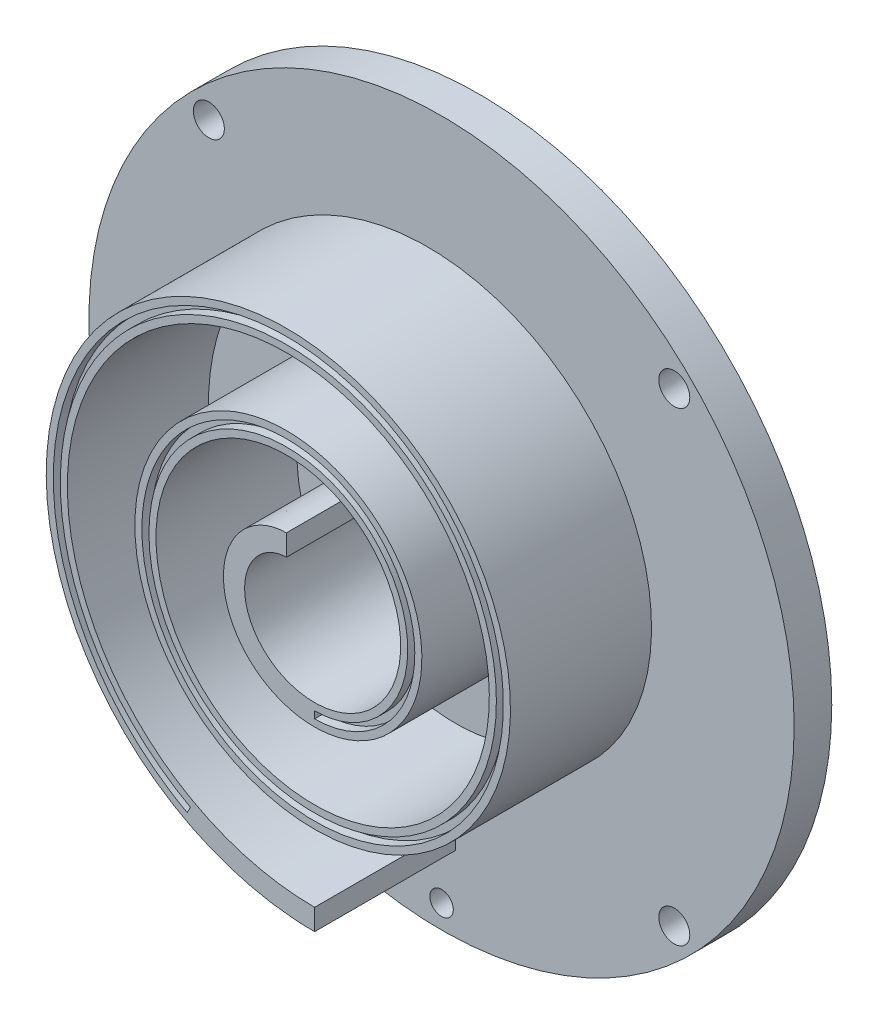
SolidWorks part; units mm, degrees
ref_plane "前视基准面" through (0, 0, 0) normal (0, 0, 1) x (1, 0, 0)
ref_plane "上视基准面" through (0, 0, 0) normal (0, 1, 0) x (1, 0, 0)
ref_plane "右视基准面" through (0, 0, 0) normal (1, 0, 0) x (0, 0, -1)
sketch "草图1" plane through (0, 0, 0) normal (0, 0, 1) x (1, 0, 0)
  circle A0 centre (0, 0) radius 75
extrude "凸台-拉伸1" add sketch "草图1" along normal blind 8
ref_plane "基准面1" through (0, 0, 8) normal (0, 0, 1) x (1, 0, 0)
sketch "草图2" plane through (0, 0, 0) normal (0, 0, 1) x (1, 0, 0)
  circle A0 centre (0, 0) radius 5
extrude "切除-拉伸1" cut sketch "草图2" along normal through all
sketch "草图3" plane through (0, 0, 8) normal (0, 0, 1) x (1, 0, 0)
  line L0 (3, -58.7987) -> (3, -54.2987)
  line L1 (-3, 7.1748) -> (-3, 11.6748)
  spline S0 degree 3 poles (-3, 11.6748) (-3.2407, 11.6705) (-3.7258, 11.6618) (-4.4563, 11.5916) (-5.1925, 11.4783) (-5.9313, 11.3168) (-6.6697, 11.1074) (-7.4046, 10.8494) (-8.1326, 10.5424) (-8.8506, 10.1863) (-9.5552, 9.7812) (-10.2431, 9.3275) (-10.9109, 8.8256) (-11.5552, 8.2764) (-12.1728, 7.6809) (-12.7604, 7.0403) (-13.3147, 6.3561) (-13.8325, 5.63) (-14.3109, 4.8639) (-14.7467, 4.06) (-15.1372, 3.2207) (-15.4797, 2.3485) (-15.7715, 1.4461) (-16.0102, 0.5166) (-16.1936, -0.4368) (-16.3196, -1.411) (-16.3865, -2.4023) (-16.3925, -3.4071) (-16.3362, -4.4217) (-16.2165, -5.4421) (-16.0325, -6.4644) (-15.7834, -7.4845) (-15.4689, -8.4982) (-15.0889, -9.5013) (-14.6434, -10.4894) (-14.1329, -11.4584) (-13.558, -12.404) (-12.9198, -13.3217) (-12.2196, -14.2075) (-11.4588, -15.0571) (-10.6393, -15.8664) (-9.7631, -16.6313) (-8.8328, -17.348) (-7.851, -18.0126) (-6.8205, -18.6215) (-5.7445, -19.1712) (-4.6265, -19.6584) (-3.4701, -20.08) (-2.2792, -20.4331) (-1.0579, -20.715) (0.1896, -20.9234) (1.4587, -21.0561) (2.7449, -21.1112) (4.0433, -21.0872) (5.3491, -20.9826) (6.6572, -20.7966) (7.9625, -20.5284) (9.2598, -20.1778) (10.5439, -19.7447) (11.8094, -19.2293) (13.0512, -18.6325) (14.2639, -17.9551) (15.4423, -17.1985) (16.5811, -16.3644) (17.6754, -15.4549) (18.7201, -14.4721) (19.7103, -13.419) (20.6413, -12.2984) (21.5085, -11.1137) (22.3075, -9.8686) (23.0342, -8.5669) (23.6845, -7.213) (24.2549, -5.8112) (24.7419, -4.3664) (25.1423, -2.8836) (25.4533, -1.3679) (25.6723, 0.1752) (25.7972, 1.7401) (25.8262, 3.3209) (25.7576, 4.9119) (25.5905, 6.5069) (25.324, 8.0999) (24.9577, 9.6844) (24.4918, 11.2544) (23.9266, 12.8035) (23.263, 14.3253) (22.5021, 15.8137) (21.6457, 17.2623) (20.6957, 18.6651) (19.6546, 20.0159) (18.5251, 21.3088) (17.3106, 22.5381) (16.0146, 23.6981) (14.641, 24.7835) (13.1941, 25.789) (11.6787, 26.7098) (10.0996, 27.5412) (8.4622, 28.2789) (6.7722, 28.9188) (5.0352, 29.4571) (3.2576, 29.8907) (1.4455, 30.2164) (-0.3943, 30.4317) (-2.2551, 30.5344) (-4.13, 30.5227) (-6.012, 30.3953) (-7.8938, 30.1513) (-9.7682, 29.7902) (-11.6279, 29.3121) (-13.4655, 28.7173) (-15.2737, 28.0068) (-17.0451, 27.1821) (-18.7726, 26.2448) (-20.449, 25.1974) (-22.0672, 24.0427) (-23.6203, 22.7837) (-25.1016, 21.4243) (-26.5045, 19.9684) (-27.8229, 18.4206) (-29.0508, 16.7859) (-30.1822, 15.0695) (-31.2119, 13.2772) (-32.1348, 11.415) (-32.9462, 9.4892) (-33.6417, 7.5067) (-34.2173, 5.4744) (-34.6697, 3.3996) (-34.9958, 1.2898) (-35.1928, -0.8473) (-35.2588, -3.0038) (-35.1921, -5.1715) (-34.9916, -7.3423) (-34.6566, -9.5079) (-34.187, -11.66) (-33.5833, -13.79) (-32.8463, -15.8897) (-31.9776, -17.9507) (-30.9791, -19.9646) (-29.8534, -21.9233) (-28.6034, -23.8188) (-27.2328, -25.643) (-25.7456, -27.3884) (-24.1463, -29.0474) (-22.44, -30.6129) (-20.6321, -32.0779) (-18.7285, -33.4359) (-16.7357, -34.6805) (-14.6604, -35.806) (-12.5097, -36.8069) (-10.2912, -37.6782) (-8.0127, -38.4153) (-5.6823, -39.014) (-3.3085, -39.4709) (-0.9, -39.7828) (1.5345, -39.9472) (3.9857, -39.9621) (6.4445, -39.826) (8.9016, -39.5381) (11.3475, -39.098) (13.7727, -38.5061) (16.168, -37.7633) (18.5237, -36.8709) (20.8306, -35.8312) (23.0794, -34.6467) (25.2609, -33.3206) (27.3664, -31.8569) (29.387, -30.2597) (31.3142, -28.5342) (32.8341, -26.9953) (33.9954, -25.706) (34.8391, -24.7095) (35.6535, -23.6854) (36.4379, -22.6345) (37.1913, -21.5578) (37.9128, -20.456) (38.6017, -19.3303) (39.2572, -18.1815) (39.8784, -17.0106) (40.4646, -15.8187) (41.0152, -14.6068) (41.5294, -13.3759) (42.0067, -12.1273) (42.4463, -10.8619) (42.8478, -9.5809) (43.2105, -8.2856) (43.534, -6.9769) (43.8178, -5.6562) (44.0615, -4.3246) (44.2647, -2.9834) (44.4269, -1.6337) (44.5479, -0.277) (44.6274, 1.0857) (44.6652, 2.453) (44.6609, 3.8237) (44.6146, 5.1963) (44.5259, 6.5698) (44.3949, 7.9426) (44.2216, 9.3137) (44.0057, 10.6815) (43.7476, 12.0449) (43.4471, 13.4024) (43.1044, 14.7528) (42.7196, 16.0948) (42.293, 17.4271) (41.8249, 18.7483) (41.3153, 20.0571) (40.7648, 21.3523) (40.1736, 22.6326) (39.5422, 23.8967) (38.8709, 25.1433) (38.1603, 26.3711) (37.4109, 27.579) (36.6232, 28.7657) (35.7979, 29.9299) (34.9355, 31.0706) (34.0368, 32.1864) (33.1024, 33.2763) (32.1331, 34.3391) (31.1298, 35.3737) (30.0931, 36.379) (29.024, 37.354) (27.9233, 38.2975) (26.7921, 39.2086) (25.6311, 40.0863) (24.4415, 40.9295) (23.2242, 41.7375) (21.9803, 42.5092) (20.7109, 43.2438) (19.4171, 43.9405) (18.0999, 44.5984) (16.7607, 45.2168) (15.4005, 45.7949) (14.0205, 46.332) (12.6221, 46.8275) (11.2065, 47.2807) (9.7749, 47.6911) (8.3286, 48.0581) (6.8691, 48.3811) (5.3975, 48.6598) (3.9153, 48.8936) (2.4238, 49.0821) (0.9244, 49.2252) (-0.5815, 49.3223) (-2.0925, 49.3733) (-3.6072, 49.3779) (-5.1241, 49.336) (-6.6418, 49.2474) (-8.1589, 49.112) (-9.674, 48.9299) (-11.1855, 48.7009) (-12.6921, 48.4251) (-14.1923, 48.1027) (-15.6846, 47.7338) (-17.1676, 47.3184) (-18.6399, 46.8569) (-20.1, 46.3496) (-21.5465, 45.7967) (-22.9779, 45.1986) (-24.3929, 44.5557) (-25.7901, 43.8685) (-27.168, 43.1373) (-28.5253, 42.3629) (-29.8606, 41.5458) (-31.1725, 40.6865) (-32.4599, 39.7857) (-33.7212, 38.8442) (-34.9553, 37.8627) (-36.1608, 36.842) (-37.3365, 35.7828) (-38.4813, 34.6862) (-39.5938, 33.5529) (-40.673, 32.384) (-41.7177, 31.1804) (-42.7267, 29.9431) (-43.6991, 28.6732) (-44.6336, 27.3718) (-45.5294, 26.04) (-46.3854, 24.679) (-47.2007, 23.2899) (-47.9744, 21.8739) (-48.7055, 20.4324) (-49.3933, 18.9666) (-50.0369, 17.4778) (-50.6355, 15.9673) (-51.1885, 14.4365) (-51.6952, 12.8867) (-52.1549, 11.3195) (-52.567, 9.7361) (-52.931, 8.1381) (-53.2463, 6.5269) (-53.5125, 4.9041) (-53.7292, 3.271) (-53.896, 1.6292) (-54.0125, -0.0197) (-54.0785, -1.6743) (-54.0937, -3.3329) (-54.058, -4.9941) (-53.9713, -6.6561) (-53.8333, -8.3176) (-53.6441, -9.9768) (-53.4037, -11.6323) (-53.1122, -13.2823) (-52.7695, -14.9255) (-52.376, -16.5601) (-51.9318, -18.1845) (-51.4372, -19.7973) (-50.8923, -21.3968) (-50.2977, -22.9815) (-49.6537, -24.5499) (-48.9607, -26.1003) (-48.2193, -27.6312) (-47.43, -29.1412) (-46.5933, -30.6288) (-45.7099, -32.0924) (-44.7805, -33.5306) (-43.8058, -34.9419) (-42.7866, -36.3249) (-41.7237, -37.6782) (-40.618, -39.0005) (-39.4704, -40.2903) (-38.2818, -41.5464) (-37.0533, -42.7674) (-35.7858, -43.9521) (-34.4804, -45.0992) (-33.1383, -46.2076) (-31.7606, -47.2759) (-30.3484, -48.3032) (-28.9031, -49.2882) (-27.4259, -50.23) (-25.9181, -51.1275) (-24.381, -51.9796) (-22.8159, -52.7855) (-21.2243, -53.5442) (-19.6076, -54.2549) (-17.9673, -54.9167) (-16.3047, -55.5289) (-14.6215, -56.0907) (-12.9192, -56.6014) (-11.1992, -57.0603) (-9.4632, -57.4669) (-7.7129, -57.8207) (-5.9497, -58.121) (-4.1753, -58.3675) (-2.3914, -58.56) (-0.5996, -58.6968) (1.1984, -58.7827) (2.3992, -58.7934) (3, -58.7987) knots 0 0 0 0 0.001304 0.002629 0.003974 0.00534 0.006726 0.008132 0.009559 0.011006 0.012474 0.013962 0.01547 0.016999 0.018548 0.020118 0.021708 0.023318 0.024949 0.0266 0.028272 0.029964 0.031677 0.03341 0.035163 0.036937 0.038731 0.040545 0.04238 0.044235 0.046111 0.048007 0.049924 0.051861 0.053818 0.055796 0.057794 0.059812 0.061851 0.063911 0.06599 0.06809 0.070211 0.072352 0.074513 0.076695 0.078897 0.08112 0.083363 0.085626 0.08791 0.090214 0.092539 0.094884 0.097249 0.099635 0.102042 0.104468 0.106915 0.109383 0.111871 0.114379 0.116908 0.119457 0.122026 0.124616 0.127226 0.129857 0.132508 0.13518 0.137871 0.140584 0.143317 0.14607 0.148843 0.151637 0.154451 0.157286 0.160141 0.163017 0.165913 0.168829 0.171766 0.174723 0.177701 0.180699 0.183717 0.186756 0.189815 0.192895 0.195995 0.199115 0.202256 0.205417 0.208599 0.211801 0.215023 0.218266 0.22153 0.224813 0.228117 0.231442 0.234787 0.238152 0.241538 0.244944 0.24837 0.251817 0.255284 0.258772 0.26228 0.265809 0.269358 0.272927 0.276517 0.280127 0.283757 0.287408 0.29108 0.294772 0.298484 0.302216 0.305969 0.309743 0.313536 0.317351 0.321185 0.32504 0.328916 0.332811 0.336728 0.340664 0.344621 0.348599 0.352597 0.356615 0.360654 0.364713 0.368792 0.372892 0.377012 0.381153 0.385314 0.389495 0.393697 0.39792 0.402162 0.406425 0.410709 0.415013 0.419337 0.423682 0.428047 0.432433 0.436839 0.441265 0.445712 0.450179 0.454666 0.459174 0.463703 0.468252 0.472821 0.47741 0.48202 0.486651 0.491302 0.495973 0.500664 0.503018 0.505377 0.507741 0.51011 0.512484 0.514863 0.517248 0.519637 0.522032 0.524431 0.526836 0.529246 0.531661 0.534081 0.536506 0.538936 0.541372 0.543812 0.546258 0.548709 0.551164 0.553625 0.556091 0.558562 0.561038 0.56352 0.566006 0.568498 0.570994 0.573496 0.576003 0.578515 0.581032 0.583554 0.586081 0.588613 0.591151 0.593693 0.596241 0.598793 0.601351 0.603914 0.606482 0.609055 0.611634 0.614217 0.616805 0.619399 0.621997 0.624601 0.62721 0.629824 0.632443 0.635067 0.637696 0.640331 0.64297 0.645615 0.648264 0.650919 0.653579 0.656244 0.658914 0.661589 0.664269 0.666955 0.669645 0.672341 0.675041 0.677747 0.680458 0.683174 0.685895 0.688621 0.691353 0.694089 0.69683 0.699577 0.702329 0.705085 0.707847 0.710614 0.713386 0.716164 0.718946 0.721733 0.724526 0.727323 0.730126 0.732934 0.735747 0.738565 0.741388 0.744216 0.74705 0.749888 0.752731 0.75558 0.758434 0.761293 0.764157 0.767026 0.7699 0.772779 0.775663 0.778553 0.781447 0.784347 0.787252 0.790162 0.793076 0.795997 0.798922 0.801852 0.804787 0.807728 0.810673 0.813624 0.81658 0.819541 0.822507 0.825478 0.828454 0.831435 0.834421 0.837413 0.840409 0.843411 0.846418 0.84943 0.852447 0.855469 0.858496 0.861528 0.864566 0.867608 0.870656 0.873709 0.876766 0.879829 0.882897 0.88597 0.889049 0.892132 0.89522 0.898314 0.901412 0.904516 0.907625 0.910739 0.913858 0.916982 0.920111 0.923246 0.926385 0.92953 0.932679 0.935834 0.938994 0.942159 0.945329 0.948504 0.951684 0.954869 0.95806 0.961255 0.964456 0.967662 0.970873 0.974089 0.97731 0.980536 0.983767 0.987004 0.990245 0.993492 0.996743 1 1 1 1
  spline S1 degree 3 poles (3, -54.2987) (2.4452, -54.2938) (1.3365, -54.2839) (-0.3236, -54.2046) (-1.9777, -54.0783) (-3.6243, -53.9006) (-5.262, -53.6732) (-6.889, -53.396) (-8.5041, -53.0696) (-10.1056, -52.6945) (-11.6922, -52.2711) (-13.2623, -51.8001) (-14.8145, -51.2821) (-16.3475, -50.7176) (-17.8598, -50.1075) (-19.3501, -49.4523) (-20.817, -48.753) (-22.2593, -48.0104) (-23.6757, -47.2251) (-25.0649, -46.3983) (-26.4257, -45.5308) (-27.7569, -44.6235) (-29.0574, -43.6774) (-30.326, -42.6937) (-31.5616, -41.6733) (-32.7633, -40.6173) (-33.9299, -39.5269) (-35.0605, -38.4032) (-36.1542, -37.2474) (-37.21, -36.0608) (-38.2272, -34.8444) (-39.2048, -33.5997) (-40.1421, -32.3278) (-41.0383, -31.0301) (-41.8927, -29.7079) (-42.7048, -28.3625) (-43.4738, -26.9953) (-44.1992, -25.6077) (-44.8804, -24.201) (-45.5171, -22.7766) (-46.1086, -21.336) (-46.6547, -19.8806) (-47.155, -18.4118) (-47.6092, -16.931) (-48.017, -15.4397) (-48.3782, -13.9394) (-48.6926, -12.4314) (-48.9602, -10.9173) (-49.1807, -9.3985) (-49.3543, -7.8764) (-49.4808, -6.3526) (-49.5604, -4.8284) (-49.5931, -3.3053) (-49.5791, -1.7847) (-49.5187, -0.2682) (-49.4119, 1.243) (-49.259, 2.7475) (-49.0605, 4.2437) (-48.8167, 5.7303) (-48.5279, 7.206) (-48.1946, 8.6693) (-47.8172, 10.1191) (-47.3964, 11.5538) (-46.9326, 12.9723) (-46.4265, 14.3733) (-45.8788, 15.7554) (-45.2899, 17.1175) (-44.6608, 18.4583) (-43.9922, 19.7767) (-43.2847, 21.0715) (-42.5393, 22.3415) (-41.7568, 23.5857) (-40.9381, 24.8029) (-40.0841, 25.9922) (-39.1957, 27.1524) (-38.2739, 28.2827) (-37.3197, 29.382) (-36.3342, 30.4495) (-35.3184, 31.4842) (-34.2734, 32.4854) (-33.2002, 33.4521) (-32.1, 34.3836) (-30.974, 35.2792) (-29.8233, 36.1381) (-28.6492, 36.9597) (-27.4527, 37.7433) (-26.2352, 38.4884) (-24.9978, 39.1944) (-23.7419, 39.8608) (-22.4686, 40.4871) (-21.1793, 41.0729) (-19.8753, 41.6178) (-18.5578, 42.1214) (-17.2281, 42.5834) (-15.8876, 43.0036) (-14.5375, 43.3817) (-13.1792, 43.7175) (-11.814, 44.0109) (-10.4433, 44.2618) (-9.0683, 44.4701) (-7.6903, 44.6358) (-6.3107, 44.7589) (-4.9308, 44.8394) (-3.5519, 44.8775) (-2.1753, 44.8733) (-0.8024, 44.827) (0.5658, 44.7388) (1.9277, 44.6089) (3.2822, 44.4376) (4.628, 44.2253) (5.964, 43.9724) (7.2887, 43.6792) (8.6011, 43.3462) (9.9, 42.9738) (11.1841, 42.5627) (12.4524, 42.1133) (13.7037, 41.6263) (14.9368, 41.1022) (16.1507, 40.5417) (17.3443, 39.9455) (18.5166, 39.3143) (19.6665, 38.6488) (20.7931, 37.9499) (21.8953, 37.2183) (22.9723, 36.4549) (24.0231, 35.6605) (25.0468, 34.836) (26.0427, 33.9823) (27.0097, 33.1004) (27.9473, 32.1913) (28.8545, 31.2558) (30.0215, 29.9762) (31.4013, 28.316) (32.9267, 26.233) (34.3153, 24.0698) (35.5632, 21.8355) (36.6669, 19.539) (37.6234, 17.1896) (38.4304, 14.7967) (39.0862, 12.3697) (39.5897, 9.9181) (39.9403, 7.4515) (40.1381, 4.9792) (40.1837, 2.5108) (40.0784, 0.0556) (39.8238, -2.3774) (39.4224, -4.779) (38.8771, -7.1405) (38.1912, -9.4532) (37.3686, -11.709) (36.4138, -13.8996) (35.3315, -16.0176) (34.1272, -18.0555) (32.8065, -20.0063) (31.3756, -21.8635) (29.8409, -23.621) (28.2093, -25.273) (26.4879, -26.8143) (24.684, -28.2402) (22.8054, -29.5463) (20.8599, -30.7288) (18.8556, -31.7846) (16.8005, -32.7109) (14.7032, -33.5054) (12.5718, -34.1664) (10.4149, -34.6928) (8.2408, -35.084) (6.0582, -35.3398) (3.8752, -35.4606) (1.7002, -35.4474) (-0.4586, -35.3017) (-2.5932, -35.0253) (-4.6958, -34.6206) (-6.7586, -34.0906) (-8.7743, -33.4386) (-10.7357, -32.6683) (-12.6359, -31.784) (-14.4684, -30.7902) (-16.2269, -29.6919) (-17.9056, -28.4944) (-19.4989, -27.2033) (-21.0017, -25.8246) (-22.4092, -24.3645) (-23.7173, -22.8294) (-24.922, -21.226) (-26.0199, -19.5612) (-27.008, -17.842) (-27.8838, -16.0756) (-28.6452, -14.2692) (-29.2907, -12.4301) (-29.8191, -10.5659) (-30.2298, -8.6837) (-30.5226, -6.7911) (-30.6978, -4.8954) (-30.756, -3.0038) (-30.6985, -1.1234) (-30.5268, 0.7386) (-30.243, 2.5754) (-29.8495, 4.3803) (-29.3491, 6.1469) (-28.7451, 7.8687) (-28.041, 9.5399) (-27.2408, 11.1546) (-26.3487, 12.7074) (-25.3693, 14.1931) (-24.3074, 15.607) (-23.1682, 16.9445) (-21.9569, 18.2014) (-20.6791, 19.3741) (-19.3407, 20.4591) (-17.9474, 21.4535) (-16.5053, 22.3545) (-15.0206, 23.16) (-13.4996, 23.8682) (-11.9485, 24.4777) (-10.3737, 24.9874) (-8.7816, 25.3968) (-7.1785, 25.7056) (-5.5706, 25.9141) (-3.9643, 26.0229) (-2.3656, 26.0329) (-0.7806, 25.9454) (0.7848, 25.7623) (2.325, 25.4855) (3.8343, 25.1174) (5.3073, 24.6609) (6.7391, 24.1188) (8.1246, 23.4947) (9.4592, 22.792) (10.7386, 22.0146) (11.9586, 21.1668) (13.1155, 20.2527) (14.2057, 19.2769) (15.2261, 18.2442) (16.1738, 17.1593) (17.0463, 16.0273) (17.8414, 14.8533) (18.5573, 13.6425) (19.1924, 12.4001) (19.7457, 11.1315) (20.2162, 9.842) (20.6036, 8.5368) (20.9076, 7.2214) (21.1286, 5.901) (21.267, 4.5807) (21.3237, 3.2657) (21.2998, 1.961) (21.1969, 0.6715) (21.0167, -0.5981) (20.7613, -1.8432) (20.433, -3.0593) (20.0342, -4.2424) (19.568, -5.3883) (19.0373, -6.4932) (18.4453, -7.5537) (17.7955, -8.5663) (17.0915, -9.5281) (16.3371, -10.4363) (15.5361, -11.2882) (14.6927, -12.0816) (13.8109, -12.8146) (12.8949, -13.4855) (11.949, -14.0929) (10.9775, -14.6356) (9.9847, -15.1128) (8.975, -15.524) (7.9527, -15.8689) (6.9221, -16.1475) (5.8874, -16.3601) (4.8528, -16.5072) (3.8224, -16.5898) (2.8002, -16.6087) (1.79, -16.5655) (0.7956, -16.4616) (-0.1794, -16.2987) (-1.1316, -16.0789) (-2.0576, -15.8044) (-2.9545, -15.4775) (-3.8193, -15.1007) (-4.6493, -14.6767) (-5.442, -14.2083) (-6.1951, -13.6986) (-6.9066, -13.1506) (-7.5746, -12.5673) (-8.1976, -11.9522) (-8.7742, -11.3084) (-9.3031, -10.6394) (-9.7837, -9.9485) (-10.215, -9.239) (-10.5968, -8.5144) (-10.9288, -7.7781) (-11.211, -7.0334) (-11.4437, -6.2836) (-11.6273, -5.5319) (-11.7624, -4.7814) (-11.85, -4.0353) (-11.891, -3.2966) (-11.8867, -2.568) (-11.8385, -1.8523) (-11.7479, -1.1521) (-11.6168, -0.4699) (-11.4468, 0.192) (-11.2401, 0.8315) (-10.9986, 1.4466) (-10.7247, 2.0355) (-10.4206, 2.5966) (-9.9821, 3.299) (-9.3721, 4.1026) (-8.5516, 4.9455) (-7.6694, 5.6534) (-6.7457, 6.224) (-5.8002, 6.6592) (-4.8518, 6.9591) (-3.9181, 7.1413) (-3.301, 7.1638) (-3, 7.1748) knots 0 0 0 0 0.003448 0.00689 0.010326 0.013756 0.01718 0.020598 0.024011 0.027418 0.030819 0.034214 0.037603 0.040986 0.044364 0.047735 0.051101 0.054461 0.057815 0.061163 0.064506 0.067842 0.071173 0.074498 0.077817 0.08113 0.084437 0.087739 0.091035 0.094324 0.097608 0.100886 0.104159 0.107425 0.110685 0.11394 0.117189 0.120432 0.123669 0.1269 0.130126 0.133345 0.136559 0.139767 0.142969 0.146165 0.149355 0.15254 0.155719 0.158891 0.162058 0.165219 0.168375 0.171524 0.174668 0.177805 0.180937 0.184063 0.187183 0.190297 0.193406 0.196509 0.199605 0.202696 0.205781 0.20886 0.211934 0.215001 0.218063 0.221119 0.224169 0.227213 0.230251 0.233283 0.23631 0.239331 0.242346 0.245355 0.248358 0.251355 0.254347 0.257332 0.260312 0.263286 0.266254 0.269216 0.272173 0.275123 0.278068 0.281007 0.28394 0.286867 0.289788 0.292703 0.295613 0.298517 0.301415 0.304307 0.307193 0.310073 0.312948 0.315816 0.318679 0.321536 0.324387 0.327232 0.330072 0.332905 0.335733 0.338555 0.341371 0.344181 0.346985 0.349784 0.352576 0.355363 0.358144 0.360919 0.363688 0.366452 0.369209 0.371961 0.374707 0.377447 0.380181 0.382909 0.385631 0.388348 0.391059 0.393764 0.396463 0.399156 0.404524 0.409869 0.41519 0.420488 0.425763 0.431014 0.436242 0.441446 0.446627 0.451785 0.456919 0.46203 0.467117 0.472181 0.477222 0.482239 0.487233 0.492204 0.497151 0.502074 0.506975 0.511852 0.516705 0.521535 0.526342 0.531125 0.535885 0.540622 0.545335 0.550025 0.554691 0.559334 0.563954 0.56855 0.573123 0.577672 0.582198 0.586701 0.59118 0.595636 0.600068 0.604477 0.608863 0.613225 0.617564 0.621879 0.626172 0.63044 0.634686 0.638907 0.643106 0.647281 0.651433 0.655561 0.659666 0.663748 0.667806 0.671841 0.675852 0.67984 0.683804 0.687746 0.691663 0.695558 0.699429 0.703277 0.707101 0.710902 0.714679 0.718433 0.722164 0.725871 0.729555 0.733215 0.736852 0.740466 0.744056 0.747623 0.751167 0.754687 0.758184 0.761657 0.765107 0.768533 0.771937 0.775316 0.778673 0.782006 0.785315 0.788601 0.791864 0.795104 0.79832 0.801512 0.804681 0.807827 0.81095 0.814049 0.817124 0.820177 0.823205 0.826211 0.829193 0.832152 0.835087 0.837999 0.840887 0.843752 0.846594 0.849413 0.852207 0.854979 0.857727 0.860452 0.863153 0.865831 0.868486 0.871117 0.873725 0.876309 0.87887 0.881408 0.883922 0.886413 0.88888 0.891324 0.893745 0.896142 0.898516 0.900866 0.903193 0.905497 0.907777 0.910034 0.912268 0.914478 0.916665 0.918828 0.920968 0.923084 0.925178 0.927247 0.929294 0.931317 0.933316 0.935292 0.937245 0.939174 0.94108 0.942963 0.944822 0.946658 0.948471 0.95026 0.952025 0.953767 0.955486 0.957182 0.958854 0.960502 0.962128 0.96373 0.965308 0.966863 0.968395 0.969903 0.971388 0.97285 0.974288 0.975703 0.977094 0.978462 0.979806 0.981128 0.982425 0.98495 0.98738 0.989717 0.991961 0.994111 0.996168 0.998131 1 1 1 1
extrude "凸台-拉伸2" add sketch "草图3" along normal blind 30
sketch "草图4" plane through (0, 0, 0) normal (0, 0, 1) x (1, 0, 0)
  circle A0 centre (49.4975, 49.4975) radius 3.3
  circle A1 centre (-49.4975, 49.4975) radius 3.3
  circle A2 centre (-49.4975, -49.4975) radius 3.3
  circle A3 centre (49.4975, -49.4975) radius 3.3
extrude "切除-拉伸2" cut sketch "草图4" along normal through all
sketch "草图5" plane through (0, 0, 0) normal (0, 0, 1) x (1, 0, 0)
  circle A0 centre (0, -70) radius 2.5
extrude "切除-拉伸3" cut sketch "草图5" along normal through all
ref_plane "基准面2" through (0, 0, 38) normal (0, 0, 1) x (1, 0, 0)
sketch "草图6" plane through (0, 0, 38) normal (0, 0, 1) x (1, 0, 0)
  line L0 (-24.1186, -50.4062) -> (-23.3995, -49.0899)
  line L1 (3, -18.0996) -> (3, -19.5996)
  spline S0 degree 3 poles (3, -19.5996) (3.309, -19.5953) (3.9294, -19.5869) (4.8611, -19.5183) (5.7953, -19.4083) (6.7298, -19.2524) (7.6625, -19.0516) (8.5911, -18.8052) (9.5134, -18.5134) (10.4272, -18.1761) (11.3303, -17.7935) (12.2203, -17.3659) (13.0951, -16.8937) (13.9523, -16.3774) (14.7898, -15.8175) (15.6054, -15.2149) (16.3968, -14.5703) (17.1619, -13.8846) (17.8987, -13.159) (18.6049, -12.3946) (19.2787, -11.5926) (19.9179, -10.7545) (20.5208, -9.8817) (21.0854, -8.9759) (21.6099, -8.0386) (22.0926, -7.0717) (22.532, -6.077) (22.9264, -5.0565) (23.2744, -4.0122) (23.5746, -2.9463) (23.8258, -1.8609) (24.0267, -0.7583) (24.1764, 0.3591) (24.2738, 1.489) (24.3181, 2.6289) (24.3086, 3.7762) (24.2447, 4.9285) (24.1259, 6.0832) (23.9518, 7.2375) (23.7222, 8.3889) (23.4371, 9.5347) (23.0963, 10.6722) (22.7001, 11.7986) (22.2488, 12.9113) (21.7427, 14.0075) (21.1825, 15.0846) (20.5688, 16.1399) (19.9025, 17.1707) (19.1844, 18.1743) (18.4158, 19.1483) (17.5977, 20.09) (16.7315, 20.9969) (15.8188, 21.8666) (14.861, 22.6967) (13.86, 23.4848) (12.8175, 24.2288) (11.7356, 24.9265) (10.6161, 25.5757) (9.4615, 26.1746) (8.2738, 26.7212) (7.0555, 27.2137) (5.8091, 27.6505) (4.5371, 28.0299) (3.2421, 28.3506) (1.9269, 28.6113) (0.5944, 28.8106) (-0.7527, 28.9477) (-2.1115, 29.0214) (-3.4789, 29.0312) (-4.8518, 28.9762) (-6.2273, 28.856) (-7.6022, 28.6702) (-8.9734, 28.4187) (-10.3378, 28.1013) (-11.692, 27.7182) (-13.033, 27.2696) (-14.3576, 26.7558) (-15.6627, 26.1776) (-16.945, 25.5355) (-18.2014, 24.8304) (-19.4289, 24.0634) (-20.6243, 23.2357) (-21.7848, 22.3484) (-22.9072, 21.4032) (-23.9887, 20.4016) (-25.0266, 19.3454) (-26.0179, 18.2365) (-26.9601, 17.077) (-27.8506, 15.869) (-28.6868, 14.6148) (-29.4665, 13.3169) (-30.1873, 11.9779) (-30.8472, 10.6003) (-31.4439, 9.1871) (-31.9757, 7.741) (-32.4408, 6.2652) (-32.8376, 4.7626) (-33.1645, 3.2365) (-33.4202, 1.6901) (-33.6036, 0.1267) (-33.7135, -1.4502) (-33.7492, -3.0372) (-33.7099, -4.6308) (-33.5951, -6.2274) (-33.4044, -7.8235) (-33.1376, -9.4154) (-32.7947, -10.9994) (-32.3758, -12.572) (-31.8813, -14.1294) (-31.3116, -15.6681) (-30.6674, -17.1844) (-29.9497, -18.6746) (-29.1593, -20.1352) (-28.2976, -21.5627) (-27.3658, -22.9535) (-26.3656, -24.3042) (-25.2986, -25.6115) (-24.1668, -26.872) (-22.9721, -28.0825) (-21.7169, -29.2399) (-20.4034, -30.3412) (-19.0341, -31.3834) (-17.6118, -32.3637) (-16.1392, -33.2794) (-14.6193, -34.128) (-13.0552, -34.9069) (-11.4499, -35.614) (-9.8069, -36.2471) (-8.1296, -36.8042) (-6.4215, -37.2834) (-4.6862, -37.6831) (-2.9274, -38.0018) (-1.1489, -38.2382) (0.6453, -38.391) (2.4514, -38.4594) (4.2654, -38.4426) (6.0833, -38.3399) (7.9009, -38.151) (9.7142, -37.8757) (11.519, -37.5139) (13.3113, -37.0659) (15.0869, -36.532) (16.8416, -35.9129) (18.5713, -35.2092) (20.2721, -34.422) (21.9398, -33.5525) (23.5704, -32.602) (25.16, -31.5721) (26.7047, -30.4646) (28.2008, -29.2813) (29.6445, -28.0246) (31.0322, -26.6966) (32.3603, -25.2998) (33.6256, -23.837) (34.8246, -22.3109) (35.9543, -20.7247) (37.0115, -19.0813) (37.9935, -17.3842) (38.8976, -15.6368) (39.721, -13.8427) (40.4616, -12.0055) (41.1169, -10.1293) (41.685, -8.2178) (42.164, -6.2753) (42.5522, -4.3057) (42.8482, -2.3135) (43.0507, -0.3029) (43.1585, 1.7216) (43.1709, 3.7556) (43.0872, 5.7947) (42.9068, 7.8341) (42.6297, 9.8694) (42.2559, 11.896) (41.7854, 13.9092) (41.2187, 15.9044) (40.5566, 17.8769) (39.7998, 19.8224) (38.9496, 21.736) (38.0071, 23.6135) (36.9739, 25.4503) (35.8518, 27.242) (34.6427, 28.9843) (33.3488, 30.673) (31.9725, 32.304) (30.5163, 33.8732) (28.983, 35.3767) (27.3757, 36.8107) (25.6973, 38.1716) (23.9514, 39.4559) (22.1413, 40.6602) (20.2708, 41.7813) (18.3436, 42.8161) (16.3639, 43.7619) (14.3356, 44.6159) (12.2631, 45.3758) (10.1507, 46.0391) (8.0029, 46.6038) (5.8244, 47.0681) (3.6199, 47.4304) (1.3941, 47.6891) (-0.848, 47.8431) (-3.1016, 47.8915) (-5.3616, 47.8335) (-7.623, 47.6685) (-9.8807, 47.3964) (-12.1297, 47.0171) (-14.3649, 46.5309) (-16.5811, 45.9381) (-18.7732, 45.2396) (-20.9363, 44.4362) (-23.0652, 43.5292) (-25.155, 42.52) (-27.2008, 41.4103) (-29.1978, 40.2019) (-31.1412, 38.8971) (-33.0262, 37.4982) (-34.8485, 36.0079) (-36.6034, 34.4288) (-38.2867, 32.7642) (-39.8943, 31.0171) (-41.422, 29.1912) (-42.866, 27.29) (-44.2226, 25.3173) (-45.4883, 23.2773) (-46.6597, 21.1741) (-47.7337, 19.0121) (-48.7072, 16.7957) (-49.5777, 14.5297) (-50.3426, 12.2189) (-50.9995, 9.8682) (-51.5464, 7.4827) (-51.9814, 5.0675) (-52.3031, 2.6279) (-52.51, 0.1691) (-52.6011, -2.3033) (-52.5756, -4.7839) (-52.4328, -7.2672) (-52.1724, -9.7477) (-51.7945, -12.2197) (-51.2992, -14.6778) (-50.687, -17.1162) (-49.9586, -19.5294) (-49.1152, -21.9119) (-48.1579, -24.2583) (-47.0883, -26.5629) (-45.9082, -28.8205) (-44.6197, -31.0258) (-43.2251, -33.1735) (-41.727, -35.2585) (-40.1282, -37.2758) (-38.4317, -39.2206) (-36.6408, -41.0881) (-34.7591, -42.8738) (-32.7902, -44.573) (-30.7386, -46.1823) (-28.6068, -47.6948) (-26.4047, -49.1167) (-24.8812, -49.976) (-24.1186, -50.4062) knots 0 0 0 0 0.002038 0.004091 0.006158 0.008241 0.010337 0.012449 0.014575 0.016716 0.018871 0.021041 0.023226 0.025425 0.027639 0.029868 0.032111 0.034369 0.036641 0.038929 0.041231 0.043547 0.045878 0.048224 0.050585 0.05296 0.05535 0.057754 0.060173 0.062607 0.065055 0.067518 0.069996 0.072488 0.074995 0.077517 0.080053 0.082604 0.08517 0.08775 0.090345 0.092955 0.095579 0.098218 0.100871 0.10354 0.106222 0.10892 0.111632 0.114359 0.1171 0.119856 0.122627 0.125413 0.128213 0.131027 0.133857 0.136701 0.139559 0.142433 0.145321 0.148223 0.15114 0.154072 0.157019 0.15998 0.162956 0.165947 0.168952 0.171972 0.175006 0.178055 0.181119 0.184197 0.18729 0.190398 0.193521 0.196658 0.199809 0.202976 0.206157 0.209352 0.212563 0.215788 0.219027 0.222281 0.22555 0.228834 0.232132 0.235445 0.238772 0.242115 0.245471 0.248843 0.252229 0.25563 0.259045 0.262475 0.26592 0.269379 0.272853 0.276342 0.279845 0.283363 0.286896 0.290443 0.294005 0.297582 0.301173 0.304779 0.308399 0.312035 0.315685 0.319349 0.323028 0.326722 0.33043 0.334154 0.337891 0.341644 0.345411 0.349192 0.352989 0.3568 0.360625 0.364466 0.368321 0.37219 0.376075 0.379974 0.383887 0.387815 0.391758 0.395716 0.399688 0.403675 0.407676 0.411692 0.415723 0.419769 0.423829 0.427904 0.431993 0.436097 0.440216 0.444349 0.448497 0.45266 0.456837 0.461029 0.465236 0.469457 0.473693 0.477943 0.482208 0.486488 0.490783 0.495092 0.499416 0.503754 0.508107 0.512475 0.516858 0.521255 0.525666 0.530093 0.534534 0.53899 0.54346 0.547945 0.552445 0.556959 0.561488 0.566031 0.57059 0.575163 0.57975 0.584352 0.588969 0.593601 0.598247 0.602908 0.607583 0.612273 0.616978 0.621697 0.626431 0.63118 0.635944 0.640722 0.645514 0.650322 0.655144 0.65998 0.664831 0.669697 0.674578 0.679473 0.684383 0.689308 0.694247 0.699201 0.704169 0.709152 0.71415 0.719163 0.72419 0.729231 0.734288 0.739359 0.744445 0.749545 0.75466 0.75979 0.764934 0.770093 0.775267 0.780455 0.785658 0.790875 0.796108 0.801354 0.806616 0.811892 0.817183 0.822488 0.827809 0.833143 0.838493 0.843857 0.849236 0.854629 0.860037 0.86546 0.870897 0.876349 0.881816 0.887297 0.892793 0.898304 0.903829 0.909369 0.914923 0.920493 0.926076 0.931675 0.937288 0.942916 0.948558 0.954216 0.959887 0.965574 0.971275 0.976991 0.982721 0.988466 0.994226 1 1 1 1
  spline S1 degree 3 poles (-23.3995, -49.0899) (-24.1416, -48.6712) (-25.6239, -47.835) (-27.7666, -46.4516) (-29.8407, -44.9799) (-31.8368, -43.4143) (-33.7521, -41.7613) (-35.5825, -40.0243) (-37.3244, -38.2079) (-38.9744, -36.3164) (-40.5294, -34.3545) (-41.9862, -32.3269) (-43.3423, -30.2385) (-44.5951, -28.0943) (-45.7424, -25.8994) (-46.7823, -23.6589) (-47.7128, -21.378) (-48.5327, -19.0622) (-49.2406, -16.7166) (-49.8356, -14.3468) (-50.3169, -11.9581) (-50.6841, -9.556) (-50.9371, -7.1459) (-51.0759, -4.7331) (-51.1007, -2.3232) (-51.0122, 0.0785) (-50.8112, 2.4668) (-50.4988, 4.8363) (-50.0763, 7.1819) (-49.5452, 9.4985) (-48.9073, 11.7811) (-48.1647, 14.0248) (-47.3196, 16.2247) (-46.3744, 18.3763) (-45.3319, 20.475) (-44.1949, 22.5165) (-42.9666, 24.4964) (-41.65, 26.4107) (-40.2488, 28.2556) (-38.7664, 30.0273) (-37.2068, 31.7223) (-35.5737, 33.3373) (-33.8714, 34.869) (-32.1039, 36.3146) (-30.2756, 37.6714) (-28.391, 38.9367) (-26.4545, 40.1085) (-24.4709, 41.1845) (-22.4447, 42.1629) (-20.3809, 43.0422) (-18.2841, 43.821) (-16.1593, 44.498) (-14.0115, 45.0725) (-11.8454, 45.5437) (-9.6662, 45.9113) (-7.4786, 46.1749) (-5.2878, 46.3347) (-3.0984, 46.391) (-0.9156, 46.3441) (1.256, 46.1949) (3.4115, 45.9444) (5.5463, 45.5936) (7.6556, 45.144) (9.7349, 44.5973) (11.7798, 43.9551) (13.786, 43.2197) (15.7491, 42.3931) (17.665, 41.4778) (19.5299, 40.4764) (21.3397, 39.3917) (23.0909, 38.2266) (24.7799, 36.9842) (26.4033, 35.6678) (27.9579, 34.2809) (29.4407, 32.8269) (30.8487, 31.3095) (32.1795, 29.7326) (33.4303, 28.1) (34.5991, 26.4158) (35.6837, 24.684) (36.6822, 22.9089) (37.593, 21.0947) (38.4146, 19.2456) (39.1457, 17.3661) (39.7853, 15.4606) (40.3326, 13.5334) (40.787, 11.5891) (41.1481, 9.6321) (41.4156, 7.6669) (41.5897, 5.6978) (41.6706, 3.7295) (41.6586, 1.7662) (41.5545, -0.1878) (41.3592, -2.128) (41.0736, -4.0503) (40.699, -5.9504) (40.237, -7.8243) (39.689, -9.6679) (39.057, -11.4774) (38.3429, -13.249) (37.549, -14.9788) (36.6774, -16.6634) (35.7308, -18.2993) (34.7118, -19.8832) (33.6232, -21.4119) (32.4679, -22.8823) (31.2489, -24.2917) (29.9695, -25.6372) (28.6329, -26.9163) (27.2425, -28.1266) (25.8019, -29.266) (24.3147, -30.3323) (22.7844, -31.3237) (21.2149, -32.2386) (19.6099, -33.0755) (17.9734, -33.8329) (16.3091, -34.51) (14.6211, -35.1056) (12.9133, -35.6191) (11.1896, -36.05) (9.4541, -36.3979) (7.7107, -36.6626) (5.9634, -36.8442) (4.2162, -36.9428) (2.4729, -36.959) (0.7375, -36.8933) (-0.9863, -36.7465) (-2.6947, -36.5194) (-4.3838, -36.2133) (-6.0502, -35.8295) (-7.6903, -35.3694) (-9.3005, -34.8346) (-10.8775, -34.227) (-12.418, -33.5484) (-13.9189, -32.8009) (-15.377, -31.9868) (-16.7896, -31.1085) (-18.1536, -30.1683) (-19.4666, -29.1689) (-20.7259, -28.1131) (-21.9292, -27.0037) (-23.0742, -25.8435) (-24.1587, -24.6356) (-25.181, -23.3831) (-26.1391, -22.0892) (-27.0315, -20.7572) (-27.8567, -19.3903) (-28.6134, -17.9918) (-29.3005, -16.5653) (-29.917, -15.1142) (-30.4621, -13.6418) (-30.9353, -12.1518) (-31.336, -10.6475) (-31.6639, -9.1326) (-31.919, -7.6105) (-32.1013, -6.0846) (-32.2111, -4.5586) (-32.2486, -3.0357) (-32.2146, -1.5194) (-32.1095, -0.013) (-31.9344, 1.4801) (-31.6902, 2.9568) (-31.3781, 4.4137) (-30.9995, 5.8479) (-30.5556, 7.2563) (-30.0482, 8.636) (-29.479, 9.9841) (-28.8497, 11.2979) (-28.1624, 12.5747) (-27.4191, 13.8119) (-26.6221, 15.0073) (-25.7736, 16.1584) (-24.876, 17.263) (-23.9318, 18.3192) (-22.9436, 19.3249) (-21.9139, 20.2785) (-20.8456, 21.1781) (-19.7413, 22.0224) (-18.604, 22.8099) (-17.4365, 23.5395) (-16.2418, 24.2099) (-15.0227, 24.8203) (-13.7823, 25.37) (-12.5237, 25.8581) (-11.2497, 26.2843) (-9.9635, 26.6482) (-8.6681, 26.9495) (-7.3664, 27.1883) (-6.0616, 27.3646) (-4.7566, 27.4786) (-3.4542, 27.5308) (-2.1576, 27.5216) (-0.8695, 27.4517) (0.4073, 27.3218) (1.6699, 27.1329) (2.9157, 26.886) (4.142, 26.5823) (5.3463, 26.2231) (6.526, 25.8097) (7.6787, 25.3437) (8.8021, 24.8267) (9.894, 24.2604) (10.9522, 23.6466) (11.9748, 22.9873) (12.9597, 22.2844) (13.9052, 21.5399) (14.8095, 20.7562) (15.671, 19.9353) (16.4883, 19.0795) (17.26, 18.1912) (17.9849, 17.2728) (18.6618, 16.3267) (19.2898, 15.3553) (19.8679, 14.3611) (20.3955, 13.3468) (20.8719, 12.3148) (21.2967, 11.2676) (21.6694, 10.2079) (21.9898, 9.1382) (22.258, 8.061) (22.4737, 6.979) (22.6372, 5.8946) (22.7488, 4.8103) (22.8088, 3.7286) (22.8177, 2.6519) (22.7762, 1.5827) (22.6848, 0.5233) (22.5446, -0.524) (22.3563, -1.557) (22.1211, -2.5735) (21.8401, -3.5714) (21.5144, -4.5486) (21.1455, -5.5031) (20.7347, -6.4331) (20.2836, -7.3368) (19.7936, -8.2123) (19.2664, -9.0582) (18.7038, -9.8728) (18.1074, -10.6546) (17.4792, -11.4024) (16.8209, -12.1149) (16.1346, -12.7909) (15.4221, -13.4294) (14.6855, -14.0293) (13.9268, -14.59) (13.1481, -15.1105) (12.3514, -15.5904) (11.5389, -16.029) (10.7127, -16.426) (9.8747, -16.7809) (9.0273, -17.0937) (8.1724, -17.3643) (7.3121, -17.5925) (6.4486, -17.7785) (5.5838, -17.9227) (4.7198, -18.0244) (3.8587, -18.0878) (3.2855, -18.0957) (3, -18.0996) knots 0 0 0 0 0.005852 0.011688 0.017509 0.023315 0.029106 0.034881 0.040642 0.046387 0.052116 0.057831 0.06353 0.069214 0.074882 0.080536 0.086174 0.091797 0.097404 0.102997 0.108574 0.114136 0.119682 0.125213 0.13073 0.13623 0.141716 0.147186 0.152641 0.158081 0.163505 0.168915 0.174309 0.179687 0.185051 0.190399 0.195732 0.20105 0.206352 0.211639 0.216911 0.222168 0.227409 0.232635 0.237846 0.243042 0.248222 0.253387 0.258537 0.263672 0.268791 0.273895 0.278984 0.284058 0.289116 0.294159 0.299187 0.304199 0.309196 0.314178 0.319145 0.324097 0.329033 0.333954 0.338859 0.34375 0.348625 0.353485 0.35833 0.363159 0.367973 0.372772 0.377556 0.382324 0.387077 0.391815 0.396538 0.401245 0.405937 0.410614 0.415275 0.419922 0.424553 0.429169 0.433769 0.438354 0.442924 0.447479 0.452019 0.456543 0.461052 0.465546 0.470024 0.474487 0.478935 0.483368 0.487785 0.492187 0.496574 0.500946 0.505302 0.509643 0.513969 0.51828 0.522575 0.526855 0.53112 0.53537 0.539604 0.543823 0.548027 0.552216 0.556389 0.560547 0.56469 0.568817 0.572929 0.577026 0.581108 0.585175 0.589226 0.593262 0.597282 0.601288 0.605278 0.609253 0.613213 0.617157 0.621086 0.625 0.628899 0.632782 0.63665 0.640503 0.64434 0.648163 0.65197 0.655762 0.659538 0.6633 0.667046 0.670776 0.674492 0.678192 0.681877 0.685547 0.689201 0.692841 0.696464 0.700073 0.703667 0.707245 0.710808 0.714355 0.717888 0.721405 0.724907 0.728394 0.731865 0.735321 0.738762 0.742187 0.745598 0.748993 0.752373 0.755737 0.759087 0.762421 0.765739 0.769043 0.772331 0.775604 0.778862 0.782104 0.785332 0.788544 0.79174 0.794922 0.798088 0.801239 0.804375 0.807495 0.8106 0.81369 0.816765 0.819824 0.822868 0.825897 0.828911 0.831909 0.834892 0.83786 0.840813 0.84375 0.846672 0.849579 0.85247 0.855347 0.858208 0.861053 0.863884 0.866699 0.869499 0.872284 0.875053 0.877808 0.880547 0.88327 0.885979 0.888672 0.89135 0.894012 0.89666 0.899292 0.901909 0.90451 0.907097 0.909668 0.912224 0.914764 0.91729 0.9198 0.922295 0.924774 0.927238 0.929687 0.932121 0.93454 0.936943 0.939331 0.941704 0.944061 0.946403 0.94873 0.951042 0.953339 0.95562 0.957886 0.960136 0.962372 0.964592 0.966797 0.968987 0.971161 0.97332 0.975464 0.977592 0.979706 0.981804 0.983887 0.985954 0.988007 0.990044 0.992065 0.994072 0.996063 0.998039 1 1 1 1
extrude "切除-拉伸4" cut sketch "草图6" against normal blind 2
